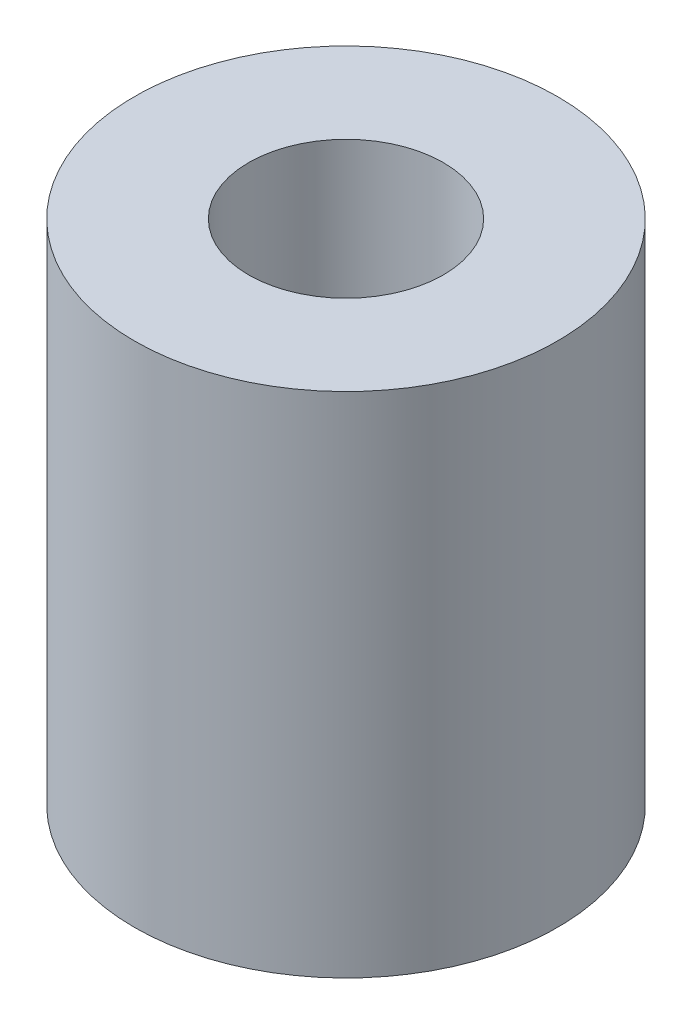
SolidWorks part; units mm, degrees
ref_plane "Płaszczyzna przednia" through (0, 0, 0) normal (0, 0, 1) x (1, 0, 0)
ref_plane "Płaszczyzna górna" through (0, 0, 0) normal (0, 1, 0) x (1, 0, 0)
ref_plane "Płaszczyzna prawa" through (0, 0, 0) normal (1, 0, 0) x (0, 0, -1)
sketch "Sketch1" plane through (0, 0, 0) normal (0, 0, 1) x (1, 0, 0)
  line L0 (0, 0) -> (0, 12) construction
  line L1 (2.3, 0) -> (5, 0)
  line L2 (5, 0) -> (5, 12)
  line L3 (5, 12) -> (2.3, 12)
  line L4 (2.3, 12) -> (2.3, 0)
  dimension "D1" = 12
  dimension "D2" = 5
  dimension "D3" = 2.3
revolve "Revolve1" add sketch "Sketch1" angle 360 about L0
